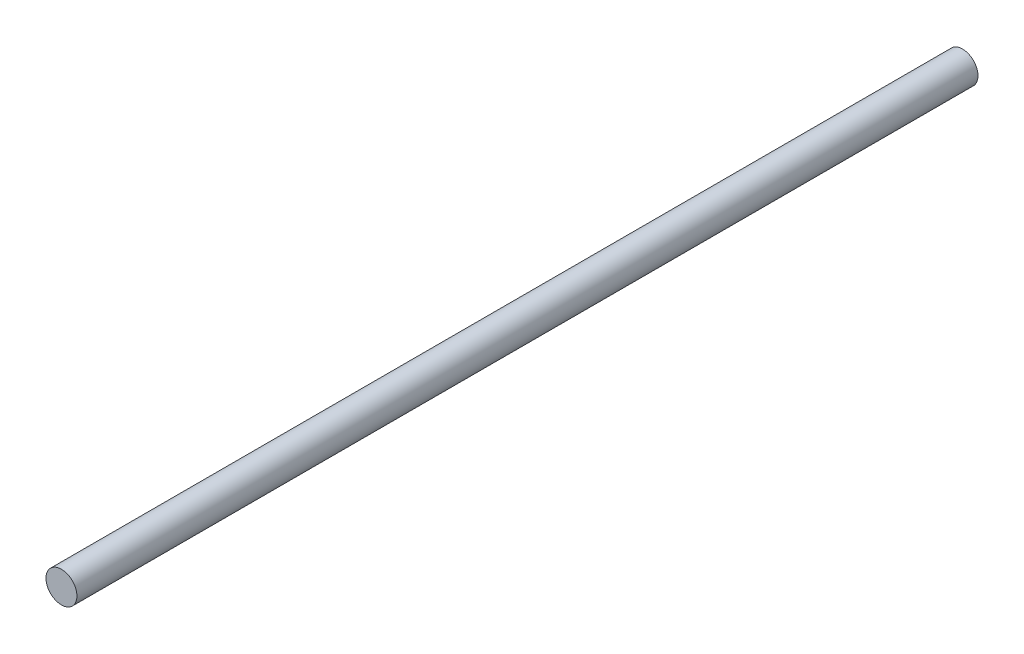
SolidWorks part; units mm, degrees
ref_plane "Front Plane" through (0, 0, 0) normal (0, 0, 1) x (1, 0, 0)
ref_plane "Top Plane" through (0, 0, 0) normal (0, 1, 0) x (1, 0, 0)
ref_plane "Right Plane" through (0, 0, 0) normal (1, 0, 0) x (0, 0, -1)
sketch "Sketch1" plane through (0, 0, 0) normal (0, 0, 1) x (1, 0, 0)
  circle A0 centre (0, 0) radius 3.175
  dimension "D1" = 6.35
extrude "Boss-Extrude1" add sketch "Sketch1" along normal blind 184.912
